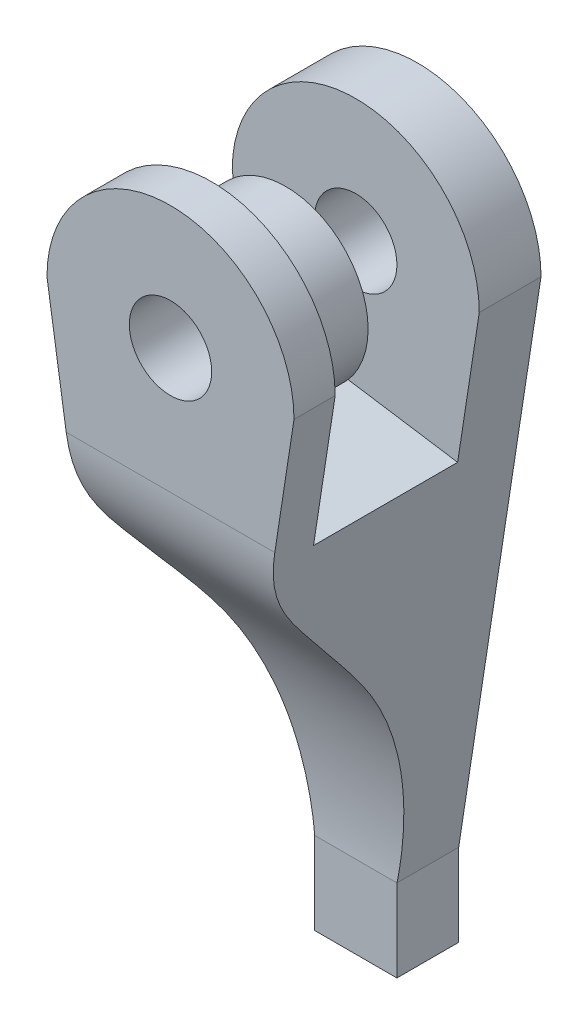
SolidWorks part; units mm, degrees
material "PLA"
ref_plane "Front" through (0, 0, 0) normal (0, 0, 1) x (1, 0, 0)
ref_plane "Top" through (0, 0, 0) normal (0, 1, 0) x (1, 0, 0)
ref_plane "Right" through (0, 0, 0) normal (1, 0, 0) x (0, 0, -1)
other "Configuration Table"
sketch "Esquisse1" plane through (0, 0, 0) normal (0, 0, 1) x (1, 0, 0)
  line L0 (-15, 0) -> (-5, -65)
  line L1 (-5, -65) -> (5, -65) construction
  line L2 (15, 0) -> (5, -65)
  line L4 (-5, -65) -> (-5, -75)
  line L5 (5, -65) -> (5, -75)
  line L6 (-5, -75) -> (5, -75)
  circle A0 centre (0, 0) radius 15
  circle A1 centre (0, 0) radius 5
  dimension "D1" = 30
  dimension "D4" = 10
  dimension "D2" = 10
  dimension "D3" = 10
  dimension "D5" = 75
extrude "Boss.-Extru.1" add sketch "Esquisse1" along normal blind 7.5 contours L0 L1 L2 A0 | L2 A0 L0 A1 | L1 L4 L6 L5
ref_plane "Plan1" through (0, 0, 25) normal (0, 0, 1) x (1, 0, 0)
sketch "Esquisse2" plane through (0, 0, 25) normal (0, 0, 1) x (1, 0, 0)
  line L0 (-15, 0) -> (-5, -65)
  line L1 (-5, -65) -> (5, -65)
  line L2 (15, 0) -> (5, -65)
  circle A0 centre (0, 0) radius 15
  circle A1 centre (0, 0) radius 5
  dimension "D1" = 30
  dimension "D4" = 10
  dimension "D2" = 65
  dimension "D3" = 10
extrude "Boss.-Extru.2" add sketch "Esquisse2" along normal blind 5 separate body contours A0 L0 L1 L2 | L2 A0 L0 A1
sketch "Esquisse3" plane through (0, 0, 25) normal (0, 0, -1) x (-1, 0, 0)
  line L0 (-12.3723, -17.0799) -> (12.9722, -13.1808)
  line L3 (-15, 0) -> (-5, -65)
  line L4 (-5, -65) -> (5, -65)
  line L5 (5, -65) -> (15, 0)
  line L6 (-15, 0) -> (-5, -65)
  line L7 (-5, -65) -> (5, -65)
  line L8 (5, -65) -> (15, 0)
  arc A1 (15, 0) -> (-15, 0) centre (0, 0) ccw
  arc A2 (15, 0) -> (-15, 0) centre (0, 0) ccw
  line M6 (-15, 0) -> (-5, -65)
  line M7 (-5, -65) -> (5, -65)
  line M8 (5, -65) -> (15, 0)
  dimension "D2" = 15
  dimension "D1" = 0
extrude "Boss.-Extru.3" add sketch "Esquisse3" along normal up to surface (17.5 mm away) contours L0 M6 M7 M8 up to face at (0, -44.1667, 7.5)
sketch "Esquisse4" plane through (0, 0, 0) normal (1, 0, 0) x (0, 0, -1)
  line L0 (-7.5, -65) -> (-7.5, -75) construction
  line L3 (-30, -15.1765) -> (-25, -15.1765) construction
  line L4 (-30, -15.1765) -> (-30, -65)
  line L5 (-30, 0) -> (-30, -65) construction
  line L7 (-30, -65) -> (-7.5, -65)
  spline S0 degree 3 poles (-7.5, -65) (-7.5, -64.789) (-5.8087, -48.1169) (-22.9477, -29.7027) (-30, -20.5547) (-30, -15.1765) knots 0 0 0 0 0.665017 0.876258 1 1 1 1
extrude "Enlèv. mat.-Extru.1" cut sketch "Esquisse4" along normal through all and the other way through all
sketch "Esquisse5" plane through (0, 0, 25) normal (0, 0, -1) x (-1, 0, 0)
  circle A0 centre (0, 0) radius 5 construction
  circle A1 centre (0, 0) radius 5
  circle A2 centre (0, 0) radius 10
  dimension "D1" = 20
extrude "Boss.-Extru.4" add sketch "Esquisse5" along normal offset from surface (9 mm away) 8.5 up to face at (5, 0, 7.5)
